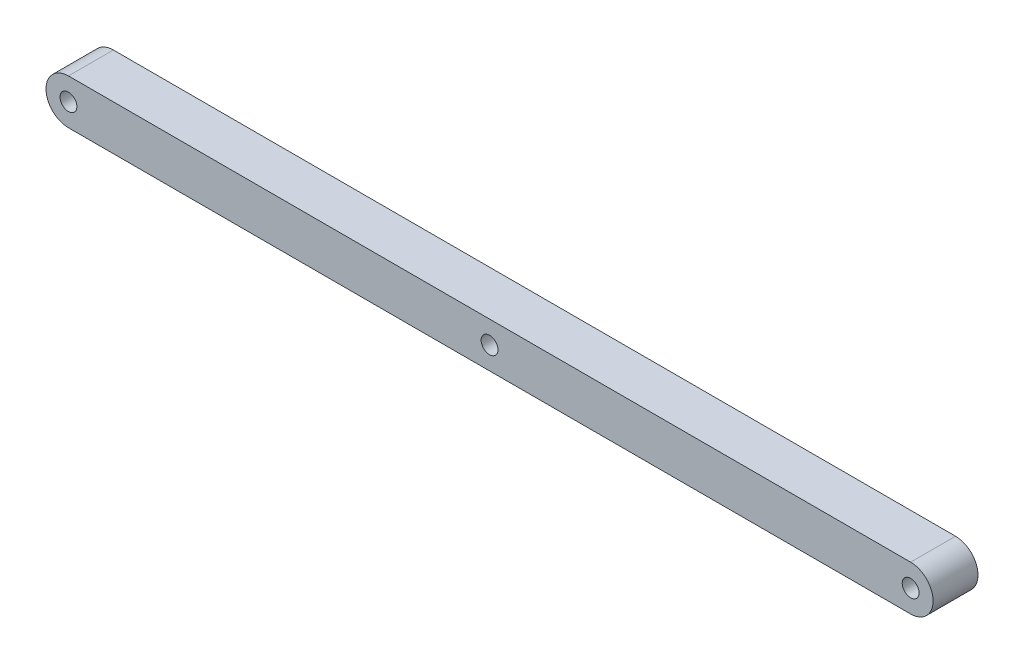
SolidWorks part; units mm, degrees
ref_plane "Front Plane" through (0, 0, 0) normal (0, 0, 1) x (1, 0, 0)
ref_plane "Top Plane" through (0, 0, 0) normal (0, 1, 0) x (1, 0, 0)
ref_plane "Right Plane" through (0, 0, 0) normal (1, 0, 0) x (0, 0, -1)
sketch "Sketch1" plane through (0, 0, 0) normal (0, 0, 1) x (1, 0, 0)
  line L0 (75, 0) -> (-75, 0) construction
  line L1 (75, -4) -> (-75, -4)
  line L2 (75, 4) -> (-75, 4)
  arc A0 (75, -4) -> (75, 4) centre (75, 0) ccw
  arc A1 (-75, 4) -> (-75, -4) centre (-75, 0) ccw
  circle A2 centre (-75, 0) radius 1.5
  circle A3 centre (75, 0) radius 1.5
  point P3 (0, 0)
  dimension "D4" = 3
  dimension "D5" = 3
  dimension "D1" = 150
  dimension "D2" = 8
  dimension "D3" = 75
extrude "Boss-Extrude1" add sketch "Sketch1" along normal blind 8
sketch "Sketch2" plane through (0, 0, 8) normal (0, 0, 1) x (1, 0, 0)
  circle A0 centre (0, 0) radius 1.5
  dimension "D1" = 3
extrude "Cut-Extrude1" cut sketch "Sketch2" against normal blind 10
